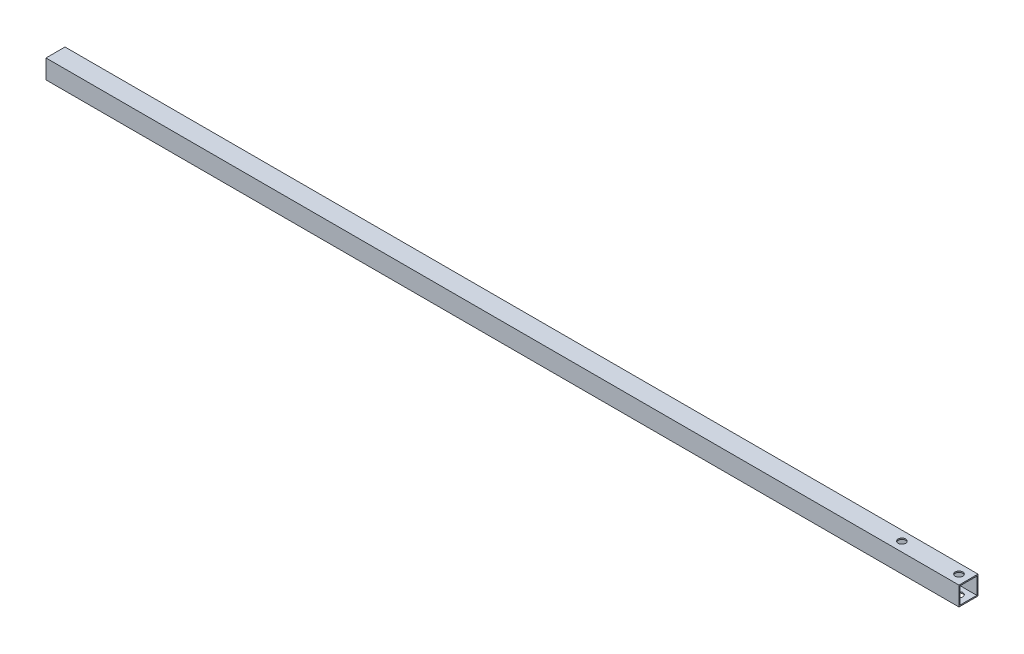
SolidWorks part; units mm, degrees
ref_plane "Front Plane" through (0, 0, 0) normal (0, 0, 1) x (1, 0, 0)
ref_plane "Top Plane" through (0, 0, 0) normal (0, 1, 0) x (1, 0, 0)
ref_plane "Right Plane" through (0, 0, 0) normal (1, 0, 0) x (0, 0, -1)
sketch "Sketch1" plane through (0, 0, 0) normal (1, 0, 0) x (0, 0, -1)
  line L0 (11.1125, -11.1125) -> (11.1125, 11.1125)
  line L1 (-12.7, -12.7) -> (12.7, -12.7)
  line L2 (-12.7, -12.7) -> (-12.7, 12.7)
  line L3 (-12.7, 12.7) -> (12.7, 12.7)
  line L4 (12.7, -12.7) -> (12.7, 12.7)
  line L5 (-12.7, -12.7) -> (12.7, 12.7) construction
  line L6 (-12.7, 12.7) -> (12.7, -12.7) construction
  line L7 (-11.1125, 11.1125) -> (11.1125, 11.1125)
  line L8 (-11.1125, -11.1125) -> (-11.1125, 11.1125)
  line L9 (-11.1125, -11.1125) -> (11.1125, -11.1125)
  point P0 (0, 0)
  dimension "D1" = 25.4
  dimension "D2" = 25.4
  dimension "D3" = 1.5875
extrude "Boss-Extrude1" add sketch "Sketch1" along normal blind 1219.2
hole_wizard "3/8 Clearance Hole1" positions "Sketch2" profile "Sketch3" hole size "3/8" standard "ANSI Inch" end condition through all
sketch "Sketch2" plane through (0, 12.7, 0) normal (0, 1, 0) x (1, 0, 0)
  line L0 (1219.2, 12.7) -> (0, 12.7) construction
  line L1 (1219.2, 12.7) -> (1219.2, -12.7) construction
  point P0 (1206.5, 0)
  point P2 (1130.3, 0)
  dimension "D1" = 12.7
  dimension "D2" = 12.7
  dimension "D3" = 12.7
  dimension "D4" = 76.2
sketch "Sketch3" plane through (1206.5, 12.7, 0) normal (1, 0, 0) x (0, 0, 1)
  line L0 (0, 0) -> (0, 25.4)
  line L1 (0, 25.4) -> (5.0419, 25.4)
  line L2 (5.0419, 25.4) -> (5.0419, 0)
  line L5 (5.0419, 0) -> (0, 0)
  line L11 (0, -6.35) -> (0, 107.95) construction
  dimension "Thru Hole Dia." = 10.0838
  dimension "Thru Hole Depth" = 25.4
